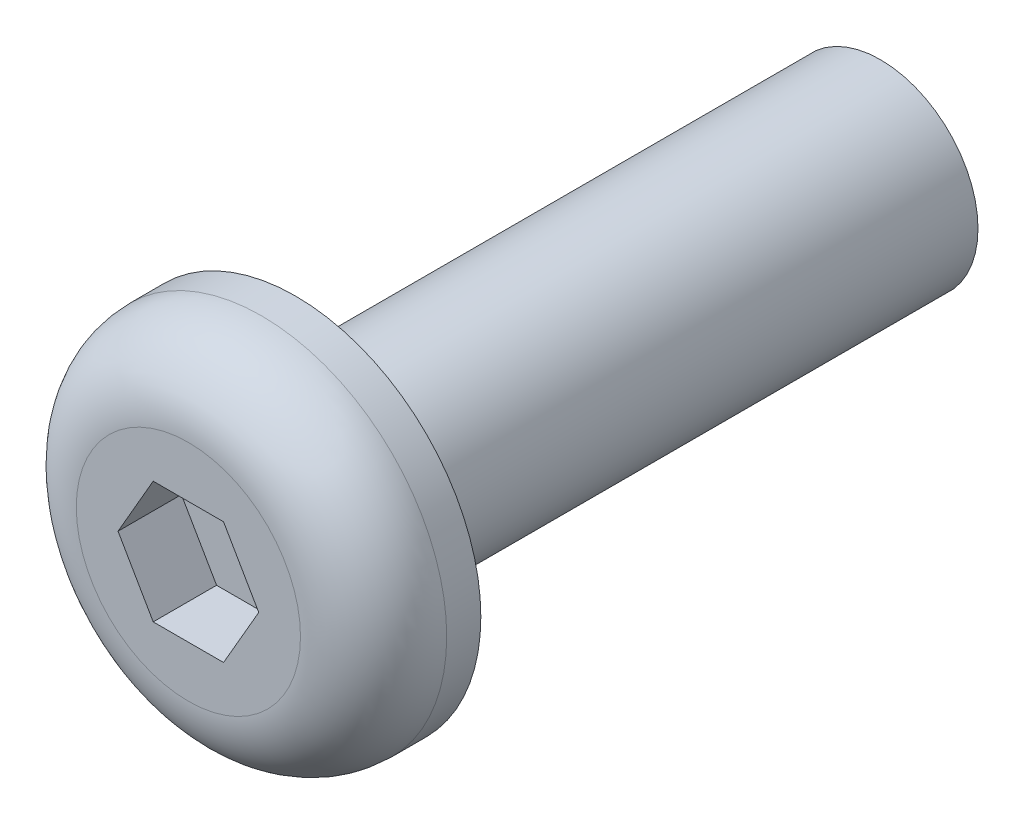
SolidWorks part; units mm, degrees
ref_plane "Front Plane" through (0, 0, 0) normal (0, 0, 1) x (1, 0, 0)
ref_plane "Top Plane" through (0, 0, 0) normal (0, 1, 0) x (1, 0, 0)
ref_plane "Right Plane" through (0, 0, 0) normal (1, 0, 0) x (0, 0, -1)
sketch "Sketch1" plane through (0, 0, 0) normal (0, 0, 1) x (1, 0, 0)
  circle A0 centre (0, 0) radius 2
extrude "Shank" add sketch "Sketch1" along normal blind 12
ref_plane "Plane_z12" through (0, 0, 12) normal (0, 0, 1) x (1, 0, 0)
sketch "Sketch2" plane through (0, 0, 12) normal (0, 0, 1) x (1, 0, 0)
  circle A0 centre (0, 0) radius 3.8
extrude "Head" add sketch "Sketch2" along normal blind 2.2
fillet "Button_round" radius 1.5 1 edges at (3.8, 0, 14.2)
ref_plane "Plane_z12_9" through (0, 0, 12.9) normal (0, 0, 1) x (1, 0, 0)
sketch "Sketch3" plane through (0, 0, 12.9) normal (0, 0, 1) x (1, 0, 0)
  line L0 (1.4434, 0) -> (0.7217, 1.25)
  line L1 (0.7217, 1.25) -> (-0.7217, 1.25)
  line L2 (-0.7217, 1.25) -> (-1.4434, 0)
  line L3 (-1.4434, 0) -> (-0.7217, -1.25)
  line L4 (-0.7217, -1.25) -> (0.7217, -1.25)
  line L5 (0.7217, -1.25) -> (1.4434, 0)
extrude "Socket" cut sketch "Sketch3" along normal blind 1.3
